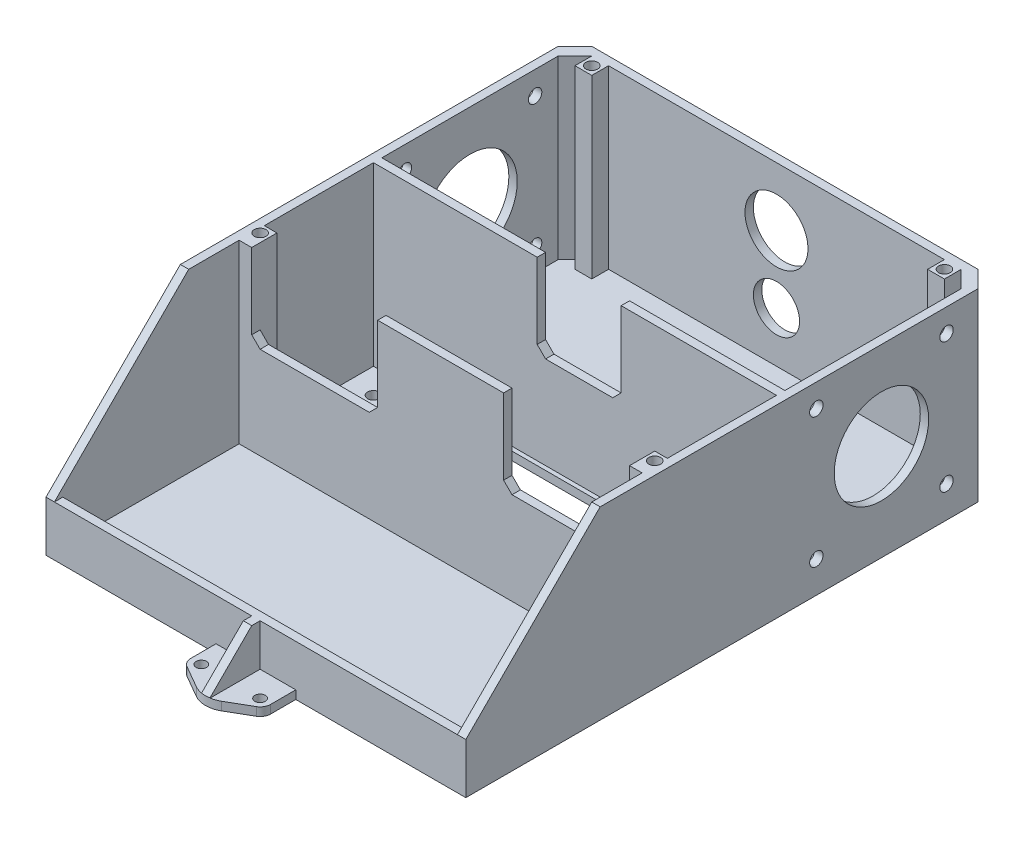
SolidWorks part; units mm, degrees
ref_plane "Front Plane" through (0, 0, 0) normal (0, 0, 1) x (1, 0, 0)
ref_plane "Top Plane" through (0, 0, 0) normal (0, 1, 0) x (1, 0, 0)
ref_plane "Right Plane" through (0, 0, 0) normal (1, 0, 0) x (0, 0, -1)
sketch "Sketch1" plane through (0, 0, 0) normal (0, 1, 0) x (1, 0, 0)
  line L1 (0, 0) -> (100, 0)
  line L2 (0, 0) -> (0, 126)
  line L3 (0, 126) -> (100, 126)
  line L4 (100, 0) -> (100, 126)
  dimension "D1" = 126
  dimension "D2" = 100
extrude "Boss-Extrude1" add sketch "Sketch1" along normal blind 2
sketch "Sketch2" plane through (0, 2, 0) normal (0, 1, 0) x (1, 0, 0)
  line L1 (0, 0) -> (100, 0)
  line L2 (0, 0) -> (0, 126)
  line L3 (0, 126) -> (100, 126)
  line L4 (100, 0) -> (100, 126)
  line L5 (2, 0) -> (98, 0)
  line L6 (2, 0) -> (2, 124)
  line L7 (2, 124) -> (98, 124)
  line L8 (98, 0) -> (98, 124)
  line L9 (2, 76) -> (98, 76)
  line L10 (2, 76) -> (2, 78)
  line L11 (2, 78) -> (98, 78)
  line L12 (98, 76) -> (98, 78)
  line L13 (98, 44) -> (2, 44)
  line L14 (98, 44) -> (98, 46)
  line L15 (98, 46) -> (2, 46)
  line L16 (2, 44) -> (2, 46)
  line M9 (0, 126) -> (0, 0)
  line M10 (0, 0) -> (100, 0)
  line M11 (100, 0) -> (100, 126)
  line M12 (100, 126) -> (0, 126)
  dimension "D1" = 2
  dimension "D2" = 2
  dimension "D3" = 2
  dimension "D4" = 0
  dimension "D5" = 48
  dimension "D6" = 2
  dimension "D7" = 2
  dimension "D8" = 30
extrude "Boss-Extrude2" add sketch "Sketch2" along normal blind 42 contours L8 L6 L7 M10 M11 M12 M9 | L10 L9 L12 L11 | L14 L13 L16 L15
chamfer "Chamfer1" distance 32 angle 45 2 edges at (99, 44, 0) (1, 44, 0)
chamfer "Chamfer2" distance 4 angle 45 4 edges at (2, 23, -124) (98, 23, -124) (0, 22, -126) (100, 22, -126)
sketch "Sketch4" plane through (2, 0, 0) normal (1, 0, 0) x (0, 0, -1)
  line L0 (120, 2) -> (120, 44) construction
  line L1 (78, 2) -> (120, 2) construction
  line L2 (99, 23) -> (56.6253, 23) construction
  line L3 (56.6253, 23) -> (92.8918, 23) construction
  line L4 (92.8918, 23) -> (99, 23) construction
  line L5 (99, 23) -> (99, 3.8095) construction
  line L6 (99, 3.8095) -> (99, 38.64) construction
  line L8 (83.5, 38.5) -> (114.5, 38.5)
  line L9 (83.5, 38.5) -> (83.5, 7.5)
  line L10 (83.5, 7.5) -> (114.5, 7.5)
  line L11 (114.5, 38.5) -> (114.5, 7.5)
  circle A0 centre (99, 23) radius 11.25
  circle A1 centre (83.5, 38.5) radius 1.6
  circle A2 centre (114.5, 38.5) radius 1.6
  circle A3 centre (114.5, 7.5) radius 1.6
  circle A4 centre (83.5, 7.5) radius 1.6
  dimension "D1" = 22.5
  dimension "D8" = 3.2
  dimension "D9" = 3.2
  dimension "D10" = 3.2
  dimension "D11" = 3.2
  dimension "D2" = 21
  dimension "D3" = 21
  dimension "D4" = 31
  dimension "D5" = 31
  dimension "D6" = 15.5
  dimension "D7" = 15.5
extrude "Cut-Extrude1" cut sketch "Sketch4" against normal through all and the other way through all contours A1 | A2 | A3 | A4 | A0
sketch "Sketch5" plane through (0, 2, 0) normal (0, 1, 0) x (1, 0, 0)
  line L0 (2, 76) -> (98, 76) construction
  line L5 (50, 0) -> (50, 72) construction
  line L6 (2, 0) -> (98, 0) construction
  line L7 (8, 70) -> (92, 70) construction
  line L8 (92, 70) -> (92, 52) construction
  line L9 (92, 52) -> (8, 52) construction
  line L10 (8, 52) -> (8, 70) construction
  line L11 (11, 61) -> (89, 61) construction
  line L13 (11, 47) -> (89, 47)
  line L14 (11, 47) -> (11, 75)
  line L15 (11, 75) -> (89, 75)
  line L16 (89, 47) -> (89, 75)
  circle A0 centre (8, 70) radius 1.4
  circle A1 centre (8, 52) radius 1.4
  circle A2 centre (92, 70) radius 1.4
  circle A3 centre (92, 52) radius 1.4
  dimension "D5" = 2.8
  dimension "D6" = 2.8
  dimension "D7" = 2.8
  dimension "D8" = 2.8
  dimension "D2" = 28
  dimension "D3" = 78
  dimension "D4" = 1
  dimension "D9" = 18
  dimension "D10" = 84
  dimension "D11" = 42
  dimension "D12" = 9
  dimension "D13" = 14
  dimension "D14" = 39
extrude "Cut-Extrude2" cut sketch "Sketch5" against normal through all
sketch "Sketch6" plane through (0, 2, 0) normal (0, 1, 0) x (1, 0, 0)
  line L0 (98, 0) -> (98, 44) construction
  line L1 (2, 0) -> (98, 0)
  line L2 (2, 0) -> (2, 2)
  line L3 (2, 2) -> (98, 2)
  line L4 (98, 0) -> (98, 2)
  dimension "D1" = 2
extrude "Boss-Extrude3" add sketch "Sketch6" along normal blind 10
sketch "Sketch9" plane through (0, 2, 0) normal (0, 1, 0) x (1, 0, 0)
  line L1 (6, 124) -> (10, 124)
  line L2 (6, 124) -> (6, 120)
  line L3 (6, 120) -> (10, 120)
  line L4 (10, 124) -> (10, 120)
  line L5 (94, 124) -> (90, 124)
  line L6 (94, 124) -> (94, 120)
  line L7 (94, 120) -> (90, 120)
  line L8 (90, 124) -> (90, 120)
  line L9 (98, 46) -> (95, 46)
  line L10 (98, 46) -> (98, 50)
  line L11 (98, 50) -> (95, 50)
  line L12 (95, 46) -> (95, 50)
  line L13 (2, 46) -> (5, 46)
  line L14 (2, 46) -> (2, 50)
  line L15 (2, 50) -> (5, 50)
  line L16 (5, 46) -> (5, 50)
  dimension "D1" = 3
  dimension "D2" = 4
  dimension "D3" = 3
  dimension "D4" = 4
  dimension "D5" = 4
  dimension "D6" = 4
  dimension "D7" = 4
  dimension "D8" = 4
extrude "Boss-Extrude5" add sketch "Sketch9" along normal blind 42
sketch "Sketch10" plane through (0, 44, 0) normal (0, 1, 0) x (1, 0, 0)
  line L0 (6, 124) -> (10, 120) construction
  line L1 (10, 120) -> (90, 120) construction
  line L2 (90, 120) -> (94, 124) construction
  line L3 (94, 124) -> (98, 50) construction
  line L4 (100, 32) -> (100, 122) construction
  line L5 (95, 46) -> (5, 46) construction
  line L6 (0, 122) -> (0, 32) construction
  line L8 (5, 50) -> (2, 50) construction
  line L9 (98, 50) -> (95, 50) construction
  circle A0 centre (3, 48) radius 1.4
  circle A1 centre (97, 48) radius 1.4
  circle A2 centre (92, 122) radius 1.4
  circle A3 centre (8, 122) radius 1.4
  dimension "D1" = 2.8
  dimension "D2" = 2.8
  dimension "D3" = 2.8
  dimension "D4" = 2.8
  dimension "D5" = 3
  dimension "D6" = 3
  dimension "D7" = 2
  dimension "D8" = 2
extrude "Cut-Extrude4" cut sketch "Sketch10" against normal blind 10
sketch "Sketch11" plane through (0, 44, 0) normal (0, 1, 0) x (1, 0, 0)
  line L5 (98, 44) -> (2, 44) construction
  line L10 (95, 46) -> (65, 46)
  line L11 (95, 46) -> (95, 44)
  line L12 (95, 44) -> (65, 44)
  line L13 (65, 46) -> (65, 44)
  line L14 (2, 78) -> (98, 78) construction
  line L15 (5, 46) -> (35, 46)
  line L16 (5, 46) -> (5, 44)
  line L17 (5, 44) -> (35, 44)
  line L18 (35, 46) -> (35, 44)
  line L19 (41, 78) -> (61, 78)
  line L20 (41, 78) -> (41, 76)
  line L21 (41, 76) -> (61, 76)
  line L22 (61, 78) -> (61, 76)
  line L23 (2, 76) -> (98, 76) construction
  dimension "D1" = 20
  dimension "D2" = 30
  dimension "D3" = 30
  dimension "D4" = 39
extrude "Cut-Extrude5" cut sketch "Sketch11" against normal blind 20
chamfer "Chamfer4" distance 2 angle 45 6 edges at (65, 24, -45) (61, 24, -77) (35, 24, -45) (5, 24, -45) (41, 24, -77) (95, 24, -45)
sketch "Sketch12" plane through (0, 0, -126) normal (0, 0, -1) x (-1, 0, 0)
  line L0 (-50, 44) -> (-50, 0) construction
  line L1 (-96, 44) -> (-4, 44) construction
  line L2 (-96, 0) -> (-4, 0) construction
  circle A0 centre (-50, 14) radius 5.5
  circle A1 centre (-50, 30) radius 7.5
  dimension "D1" = 11
  dimension "D2" = 15
  dimension "D3" = 14
  dimension "D4" = 14
extrude "Cut-Extrude6" cut sketch "Sketch12" against normal blind 2
sketch "Sketch13" plane through (0, 0, 0) normal (0, 0, 1) x (1, 0, 0)
  line L0 (50, 12) -> (50, 0) construction
  line L1 (2, 12) -> (98, 12) construction
  line L2 (0, 0) -> (100, 0) construction
  line L4 (40.5, 0) -> (59.5, 0)
  line L5 (40.5, 0) -> (40.5, 2)
  line L6 (40.5, 2) -> (59.5, 2)
  line L7 (59.5, 0) -> (59.5, 2)
  line L8 (49, 12) -> (51, 12)
  line L9 (49, 12) -> (49, 2)
  line L10 (49, 2) -> (51, 2)
  line L11 (51, 12) -> (51, 2)
  line M6 (98, 12) -> (2, 12)
  line M9 (0, 0) -> (100, 0)
  dimension "D1" = 2
  dimension "D2" = 19
  dimension "D3" = 9.5
  dimension "D4" = 2
  dimension "D5" = 1
extrude "Boss-Extrude6" add sketch "Sketch13" along normal blind 12 contours L10 L0 L4 L7 L6 | L0 L6 L5 M9 | L0 L10 L11 M6 | L0 L8 L9 L6
chamfer "Chamfer5" distance 10 angle 45 1 edges at (50, 12, 12)
sketch "Sketch14" plane through (0, 0, 0) normal (0, -1, 0) x (1, 0, 0)
  line L0 (50, 12) -> (50, -126) construction
  line L1 (40.5, 12) -> (59.5, 12) construction
  line L2 (96, -126) -> (4, -126) construction
  line L3 (40.5, 6) -> (59.5, 6) construction
  line L4 (40.5, 12) -> (40.5, 0) construction
  line L5 (59.5, 12) -> (59.5, 0) construction
  line L6 (41.75, 8.1651) -> (47, 11.1962)
  line L7 (53, 11.1962) -> (58.25, 8.1651)
  line L8 (53, 0.8038) -> (58.25, 3.8349)
  line L9 (47, 0.8038) -> (41.75, 3.8349)
  circle A0 centre (50, 6) radius 6
  circle A1 centre (43, 6) radius 2.5
  circle A2 centre (57, 6) radius 2.5
  circle A3 centre (43, 6) radius 1.25
  circle A4 centre (57, 6) radius 1.25
  line M18 (59.5, 0) -> (59.5, 12)
  line M19 (59.5, 12) -> (40.5, 12)
  line M20 (40.5, 12) -> (40.5, 0)
  dimension "D1" = 5
  dimension "D2" = 5
  dimension "D3" = 2.5
  dimension "D4" = 2.5
extrude "Cut-Extrude7" cut sketch "Sketch14" against normal blind 2.3 contours A1 L6 A0 M19 M20 | A2 A0 L7 M18 M19 | A4 | A3
